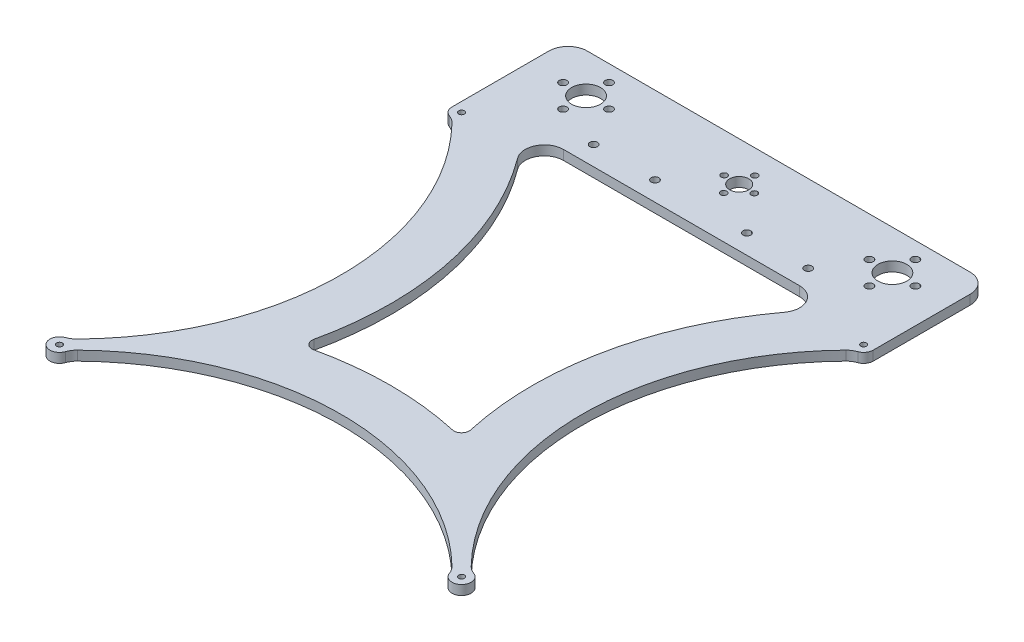
SolidWorks part; units mm, degrees
ref_plane "Front Plane" through (0, 0, 0) normal (0, 0, 1) x (1, 0, 0)
ref_plane "Top Plane" through (0, 0, 0) normal (0, 1, 0) x (1, 0, 0)
ref_plane "Right Plane" through (0, 0, 0) normal (1, 0, 0) x (0, 0, -1)
ref_plane "Plane1" through (0, 0, 0) normal (0, -1, 0) x (1, 0, 0)
sketch "Sketch1" plane through (0, 0, 0) normal (0, -1, 0) x (1, 0, 0)
  line L0 (-184.0688, -199.3698) -> (-184.0688, -249.9658)
  line L1 (-174.0688, -259.9658) -> (25.9312, -259.9658)
  line L2 (35.9312, -249.9658) -> (35.9312, -199.3698)
  line L3 (-135.7166, -209.2571) -> (-12.421, -209.2571)
  line L8 (-158.0688, -210.1276) -> (-158.0688, -233.9658) construction
  line L9 (-158.0688, -233.9658) -> (9.9312, -233.9658) construction
  line L10 (9.9312, -233.9658) -> (9.9312, -210.1276) construction
  arc A0 (9.9312, -210.1276) -> (-31.552, -51.8531) centre (128.9108, -94.3698) cw construction
  circle A1 centre (-179.0688, -199.3698) radius 1.5
  circle A2 centre (-179.0688, 10.6302) radius 1.5
  arc A3 (-171.9168, 8.481) -> (-174.3551, 12.2978) centre (-164.9277, 15.6331) cw
  arc A4 (-174.3551, 12.2978) -> (-180.7364, 5.9165) centre (-179.0688, 10.6302) ccw
  arc A5 (-180.7364, 5.9165) -> (-176.9197, 3.4782) centre (-184.0717, -3.5109) cw
  arc A6 (-176.9197, 3.4782) -> (-176.9197, -192.2179) centre (-277.0484, -94.3698) cw
  arc A7 (-176.9197, -192.2179) -> (-180.7364, -194.6561) centre (-184.0717, -185.2287) cw
  arc A8 (-180.7364, -194.6561) -> (-184.0688, -199.3698) centre (-179.0688, -199.3698) ccw
  arc A9 (-184.0688, -249.9658) -> (-174.0688, -259.9658) centre (-174.0688, -249.9658) ccw
  arc A10 (25.9312, -259.9658) -> (35.9312, -249.9658) centre (25.9312, -249.9658) ccw
  arc A11 (35.9312, -199.3698) -> (32.5989, -194.6561) centre (30.9312, -199.3698) ccw
  arc A12 (32.5989, -194.6561) -> (28.7821, -192.2179) centre (35.9341, -185.2287) cw
  arc A13 (28.7821, -192.2179) -> (28.7821, 3.4782) centre (128.9108, -94.3698) cw
  arc A14 (28.7821, 3.4782) -> (32.5989, 5.9165) centre (35.9341, -3.5109) cw
  arc A15 (32.5989, 5.9165) -> (26.2175, 12.2978) centre (30.9312, 10.6302) ccw
  arc A16 (26.2175, 12.2978) -> (23.7793, 8.481) centre (16.7901, 15.6331) cw
  arc A17 (23.7793, 8.481) -> (-171.9168, 8.481) centre (-74.0688, 108.6098) cw
  circle A18 centre (30.9312, 10.6302) radius 1.5
  circle A19 centre (30.9312, -199.3698) radius 1.5
  circle A20 centre (-74.0688, -239.3698) radius 5
  circle A21 centre (5.9312, -239.3698) radius 7.55
  circle A22 centre (-154.0688, -239.3698) radius 7.55
  circle A23 centre (-154.0688, -251.3698) radius 2
  circle A24 centre (-142.0688, -239.3698) radius 2
  circle A25 centre (-154.0688, -227.3698) radius 2
  circle A26 centre (-166.0688, -239.3698) radius 2
  circle A27 centre (5.9312, -251.3698) radius 2
  circle A28 centre (-6.0688, -239.3698) radius 2
  circle A29 centre (5.9312, -227.3698) radius 2
  circle A30 centre (17.9312, -239.3698) radius 2
  circle A31 centre (-73.9299, -247.3686) radius 1.625
  circle A32 centre (-66.07, -239.231) radius 1.625
  circle A33 centre (-74.2076, -231.371) radius 1.625
  circle A34 centre (-82.0676, -239.5087) radius 1.625
  circle A35 centre (-130.0688, -219.3698) radius 2
  arc A36 (-37.8703, -53.3954) -> (-110.2672, -53.3954) centre (-74.0688, 108.6098) cw
  arc A37 (-12.421, -209.2571) -> (-4.3908, -193.2976) centre (-12.421, -199.2571) ccw
  circle A38 centre (-98.0688, -219.3698) radius 2
  circle A39 centre (-18.0688, -219.3698) radius 2
  arc A40 (-135.7166, -209.2571) -> (-143.7468, -193.2976) centre (-135.7166, -199.2571) cw
  circle A42 centre (-50.0688, -219.3698) radius 2
  arc A43 (-115.0432, -58.1714) -> (-143.7468, -193.2976) centre (-277.0484, -94.3698) cw
  arc A44 (-31.552, -51.8531) -> (-116.5855, -51.8531) centre (-74.0688, 108.6098) cw construction
  arc A45 (-33.0944, -58.1714) -> (-37.8703, -53.3954) centre (-36.9981, -57.2992) ccw
  arc A47 (-116.5855, -51.8531) -> (-158.0688, -210.1276) centre (-277.0484, -94.3698) cw construction
  arc A48 (-115.0432, -58.1714) -> (-110.2672, -53.3954) centre (-111.1395, -57.2992) cw
  arc A50 (-4.3908, -193.2976) -> (-33.0944, -58.1714) centre (128.9108, -94.3698) cw
  arc A54 (9.9312, -233.9658) -> (9.9312, -233.9658) centre (9.9312, -233.9658) ccw construction
  arc A55 (9.9312, -210.1276) -> (9.9312, -210.1276) centre (9.9312, -210.1276) ccw construction
  arc A56 (-158.0688, -210.1276) -> (-158.0688, -210.1276) centre (-158.0688, -210.1276) ccw construction
  arc A57 (-158.0688, -210.1276) -> (-158.0688, -210.1276) centre (-158.0688, -210.1276) ccw construction
  arc A58 (9.9312, -210.1276) -> (9.9312, -210.1276) centre (9.9312, -210.1276) ccw construction
  arc A59 (-31.552, -51.8531) -> (-31.552, -51.8531) centre (-31.552, -51.8531) ccw construction
  arc A60 (-31.552, -51.8531) -> (-31.552, -51.8531) centre (-31.552, -51.8531) ccw construction
  arc A61 (-31.552, -51.8531) -> (-31.552, -51.8531) centre (-31.552, -51.8531) ccw construction
  arc A62 (-116.5855, -51.8531) -> (-116.5855, -51.8531) centre (-116.5855, -51.8531) ccw construction
  arc A63 (-116.5855, -51.8531) -> (-116.5855, -51.8531) centre (-116.5855, -51.8531) ccw construction
  arc A64 (-116.5855, -51.8531) -> (-116.5855, -51.8531) centre (-116.5855, -51.8531) ccw construction
  arc A65 (-158.0688, -233.9658) -> (-158.0688, -233.9658) centre (-158.0688, -233.9658) ccw construction
  dimension "D2" = 4
  dimension "D3" = 4
  dimension "D4" = 10
  dimension "D8" = 15.1
  dimension "D9" = 8.596
  dimension "D12" = 140
  dimension "D13" = 140
  dimension "D14" = 140
  dimension "D16" = 5
  dimension "D17" = 210
  dimension "D18" = 210
  dimension "D20" = 15.9976
  dimension "D21" = 15.9976
  dimension "D22" = 20.596
  dimension "D23" = 7.9988
  dimension "D24" = 10
  dimension "D25" = 3.25
  dimension "D26" = 32
  dimension "D27" = 48
  dimension "D28" = 32
  dimension "D29" = 40.596
  dimension "D31" = 30
  dimension "D32" = 20.596
  dimension "D33" = 4
  dimension "D34" = 3
  dimension "D5" = 50.7087
  dimension "D6" = 24
  dimension "D7" = 24
  dimension "D10" = 220
  dimension "D11" = 60.596
  dimension "D15" = 270.596
  dimension "D19" = 123.2956
  dimension "D30" = 54
  dimension "D1" = 26
extrude "Boss-Extrude1" add sketch "Sketch1" against normal blind 5
